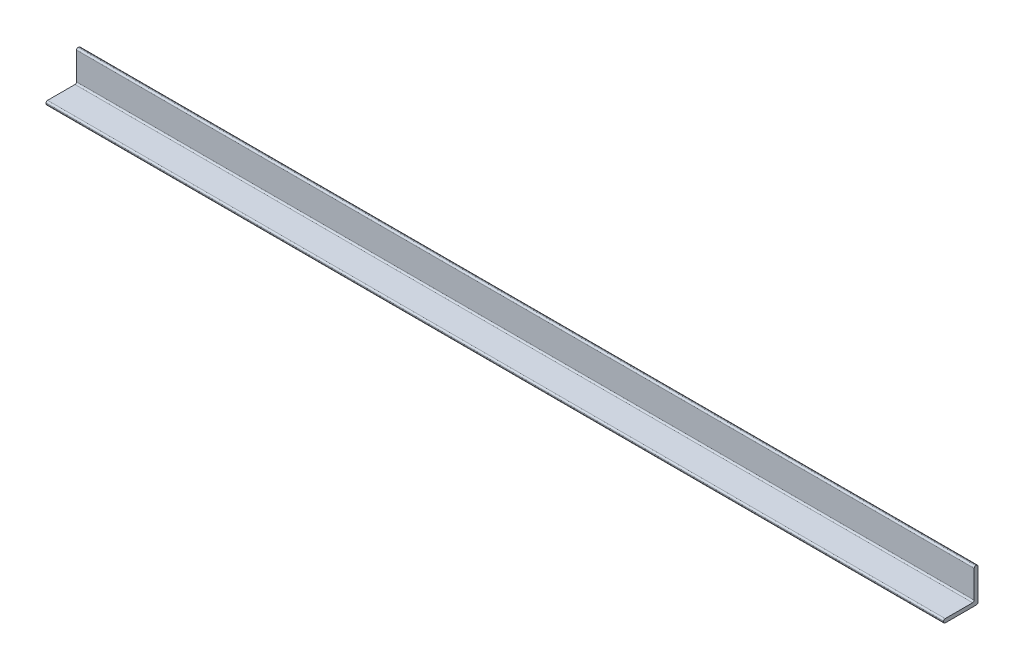
SolidWorks part; units mm, degrees
ref_plane "Front Plane" through (0, 0, 0) normal (0, 0, 1) x (1, 0, 0)
ref_plane "Top Plane" through (0, 0, 0) normal (0, 1, 0) x (1, 0, 0)
ref_plane "Right Plane" through (0, 0, 0) normal (1, 0, 0) x (0, 0, -1)
sketch "Sketch1" plane through (0, 0, 0) normal (0, 1, 0) x (1, 0, 0)
  line L1 (-294, 11.25) -> (294, 11.25)
  line L2 (-294, 11.25) -> (-294, -11.25)
  line L3 (-294, -11.25) -> (294, -11.25)
  line L4 (294, 11.25) -> (294, -11.25)
  line L5 (-294, 11.25) -> (294, -11.25) construction
  line L6 (-294, -11.25) -> (294, 11.25) construction
  point P0 (0, 0)
  dimension "D1" = 588
  dimension "D2" = 22.5
extrude "Boss-Extrude1" add sketch "Sketch1" along normal blind 2.5
sketch "Sketch2" plane through (0, 2.5, 0) normal (0, 1, 0) x (1, 0, 0)
  line L0 (294, -11.25) -> (294, 11.25) construction
  line L1 (-294, 11.25) -> (294, 11.25)
  line L2 (-294, 11.25) -> (-294, 8.75)
  line L3 (-294, 8.75) -> (294, 8.75)
  line L4 (294, 11.25) -> (294, 8.75)
  dimension "D1" = 2.5
extrude "Boss-Extrude2" add sketch "Sketch2" along normal blind 20
fillet "Fillet1" radius 1 6 edges at (0, 0, -11.25) (0, 0, 11.25) (0, 2.5, 11.25) (0, 2.5, -8.75) (0, 22.5, -8.75) (0, 22.5, -11.25)
